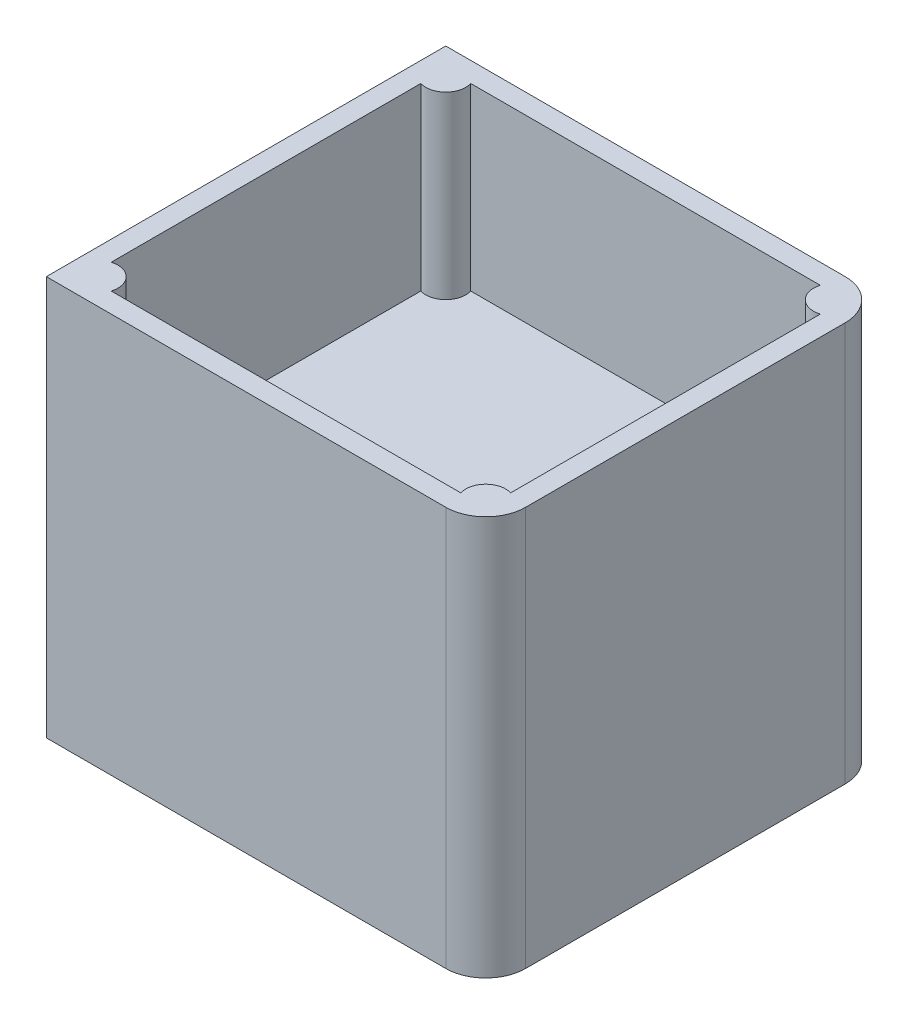
SolidWorks part; units mm, degrees
material "Custom Plastic"
ref_plane "Front Plane" through (0, 0, 0) normal (0, 0, 1) x (1, 0, 0)
ref_plane "Top Plane" through (0, 0, 0) normal (0, 1, 0) x (1, 0, 0)
ref_plane "Right Plane" through (0, 0, 0) normal (1, 0, 0) x (0, 0, -1)
sketch "Sketch1" plane through (0, 0, 0) normal (0, 1, 0) x (1, 0, 0)
  line L1 (-55, -50) -> (45, -50)
  line L2 (-55, -50) -> (-55, 50)
  line L3 (-55, 50) -> (45, 50)
  line L4 (55, -40) -> (55, 40)
  line L5 (-55, -50) -> (55, 50) construction
  line L6 (-55, 50) -> (55, -50) construction
  arc A0 (45, -50) -> (55, -40) centre (45, -40) ccw
  arc A1 (45, 50) -> (55, 40) centre (45, 40) cw
  point P0 (0, 0)
  dimension "D1" = 10
  dimension "D2" = 110
  dimension "D3" = 100
extrude "Boss-Extrude1" add sketch "Sketch1" along normal blind 100
sketch "Sketch2" plane through (0, 0, 0) normal (0, -1, 0) x (1, 0, 0)
  line L8 (-50, 45) -> (-50, -45)
  line L9 (-50, -45) -> (45, -45)
  line L10 (50, -40) -> (50, 40)
  line L11 (45, 45) -> (-50, 45)
  line L12 (-50, 45) -> (-50, -45)
  line L13 (-50, -45) -> (45, -45)
  line L14 (50, -40) -> (50, 40)
  line L15 (45, 45) -> (-50, 45)
  arc A4 (45, -45) -> (50, -40) centre (45, -40) ccw
  arc A5 (50, 40) -> (45, 45) centre (45, 40) ccw
  arc A6 (45, -45) -> (50, -40) centre (45, -40) ccw
  arc A7 (50, 40) -> (45, 45) centre (45, 40) ccw
  dimension "D1" = 5
extrude "Cut-Extrude1" cut sketch "Sketch2" against normal blind 50
sketch "Sketch3" plane through (0, 100, 0) normal (0, 1, 0) x (1, 0, 0)
  line L8 (-50, 45) -> (-50, -45)
  line L9 (-50, -45) -> (45, -45)
  line L10 (50, -40) -> (50, 40)
  line L11 (45, 45) -> (-50, 45)
  line L12 (-50, 45) -> (-50, -45)
  line L13 (-50, -45) -> (45, -45)
  line L14 (50, -40) -> (50, 40)
  line L15 (45, 45) -> (-50, 45)
  arc A4 (45, -45) -> (50, -40) centre (45, -40) ccw
  arc A5 (50, 40) -> (45, 45) centre (45, 40) ccw
  arc A6 (45, -45) -> (50, -40) centre (45, -40) ccw
  arc A7 (50, 40) -> (45, 45) centre (45, 40) ccw
  dimension "D1" = 5
extrude "Cut-Extrude2" cut sketch "Sketch3" against normal offset from surface (45 mm away) 5 up to face at (15.3452, 50, 0)
sketch "Sketch4" plane through (0, 100, 0) normal (0, 1, 0) x (1, 0, 0)
  line L0 (45, 50) -> (-55, 50) construction
  line L1 (-55, 50) -> (-55, -50) construction
  line L2 (-55, -50) -> (45, -50) construction
  arc A0 (-45, 50) -> (-55, 40) centre (-45, 40) ccw construction
  arc A1 (-55, -40) -> (-45, -50) centre (-45, -40) ccw construction
  arc A2 (45, -50) -> (55, -40) centre (45, -40) ccw construction
  circle A3 centre (48.5355, -43.5355) radius 5
  circle A4 centre (48.5355, 43.5355) radius 5
  circle A5 centre (-48.5355, -43.5355) radius 5
  circle A6 centre (-48.5355, 43.5355) radius 5
  arc A7 (55, 40) -> (45, 50) centre (45, 40) ccw construction
  point P12 (52.0711, -47.0711)
  point P20 (0, 0)
  point P25 (0, 0)
  dimension "D1" = 10
extrude "Boss-Extrude2" add sketch "Sketch4" against normal up to surface (45 mm away) up to face at (15.3452, 55, 0)
sketch "Sketch5" plane through (-55, 0, 0) normal (-1, 0, 0) x (0, 0, 1)
  line L0 (-50, 0) -> (50, 0) construction
  line L1 (-3.75, 0) -> (3.75, 0)
  line L2 (-3.75, 0) -> (-3.75, 5)
  line L3 (-3.75, 5) -> (3.75, 5)
  line L4 (3.75, 0) -> (3.75, 5)
  point P6 (0, 0)
  point P7 (0, 0)
  dimension "D1" = 5
  dimension "D2" = 7.5
extrude "Cut-Extrude4" cut sketch "Sketch5" against normal up to surface (5 mm away) up to face at (-50, 25, 0)
